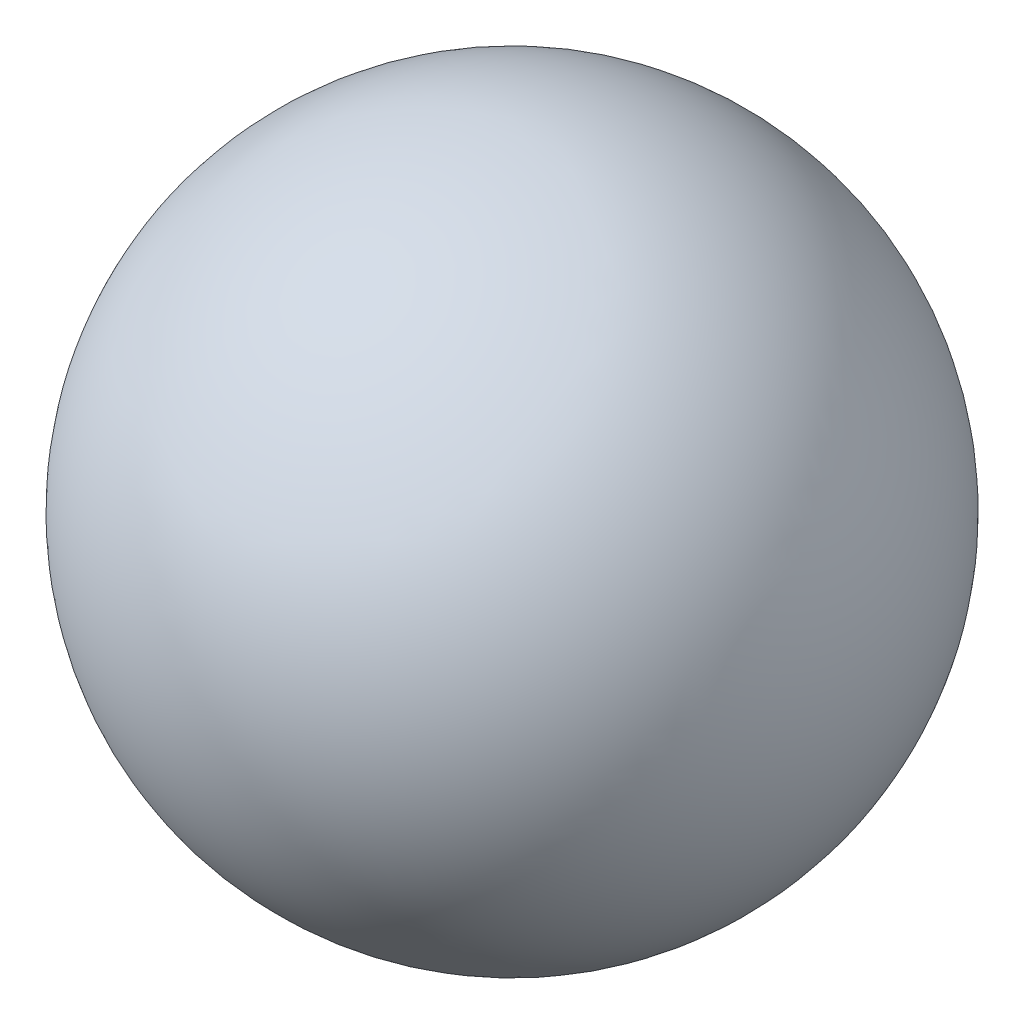
SolidWorks part; units mm, degrees
ref_plane "Plan1" through (0, 0, 0) normal (0, 0, 1) x (1, 0, 0)
ref_plane "Plan2" through (0, 0, 0) normal (0, 1, 0) x (1, 0, 0)
ref_plane "Plan3" through (0, 0, 0) normal (1, 0, 0) x (0, 0, -1)
sketch "Esquisse1" plane through (0, 0, 0) normal (0, 0, 1) x (1, 0, 0)
  line L0 (4.8879, 12.5) -> (-5.0679, 12.5) construction
  line L1 (-2.8571, 12.5) -> (2.8571, 12.5)
  arc A0 (2.8571, 12.5) -> (-2.8571, 12.5) centre (0, 12.5) ccw
  dimension "D1" = 2.8571
revolve "Base-Révolution" add sketch "Esquisse1" angle 360 about L0
